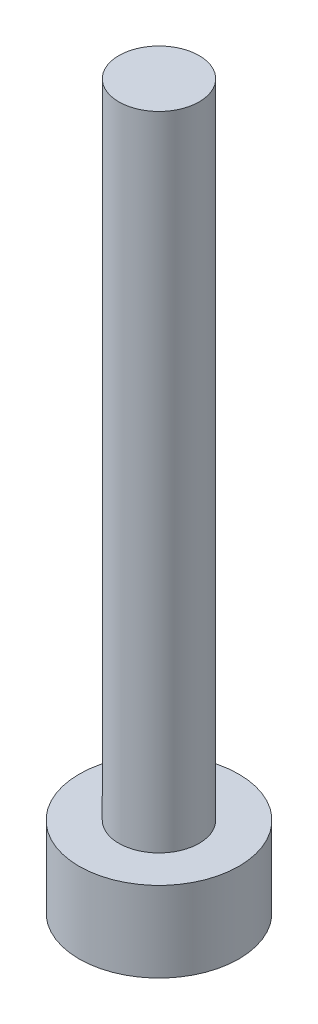
SolidWorks part; units mm, degrees
ref_plane "前视基准面" through (0, 0, 0) normal (0, 0, 1) x (1, 0, 0)
ref_plane "上视基准面" through (0, 0, 0) normal (0, 1, 0) x (1, 0, 0)
ref_plane "右视基准面" through (0, 0, 0) normal (1, 0, 0) x (0, 0, -1)
sketch "草图1" plane through (0, 0, 0) normal (0, 1, 0) x (1, 0, 0)
  circle A0 centre (0, 0) radius 1
  dimension "D1" = 2
extrude "凸台-拉伸1" add sketch "草图1" along normal blind 16
sketch "草图2" plane through (0, 0, 0) normal (0, -1, 0) x (1, 0, 0)
  circle A0 centre (0, 0) radius 1.99
  dimension "D1" = 3.98
extrude "凸台-拉伸2" add sketch "草图2" along normal blind 2
